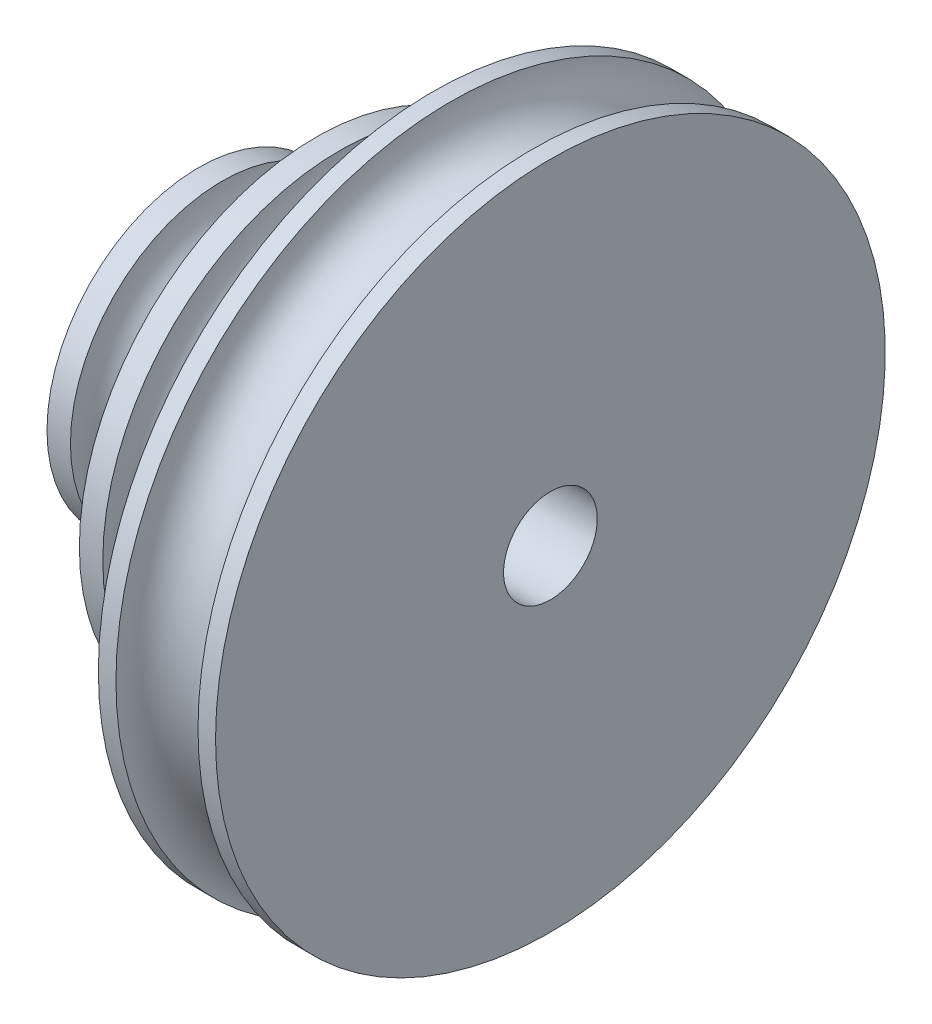
SolidWorks part; units mm, degrees
ref_plane "前视基准面" through (0, 0, 0) normal (0, 0, 1) x (1, 0, 0)
ref_plane "上视基准面" through (0, 0, 0) normal (0, 1, 0) x (1, 0, 0)
ref_plane "右视基准面" through (0, 0, 0) normal (1, 0, 0) x (0, 0, -1)
sketch "草图1" plane through (0, 0, 0) normal (0, 0, 1) x (1, 0, 0)
  line L0 (-56.8989, 20.9428) -> (82.5297, 20.9428) construction
  line L1 (-30.9942, 24.9428) -> (-30.9942, 33.8952)
  line L2 (-30.9942, 33.8952) -> (-20.9942, 33.8952)
  line L3 (-20.9942, 33.8952) -> (-20.9942, 41.1333)
  line L4 (-20.9942, 41.1333) -> (-10.9942, 41.1333)
  line L5 (-10.9942, 41.1333) -> (-10.9942, 49.5143)
  line L6 (-10.9942, 49.5143) -> (-0.9942, 49.5143)
  line L7 (-0.9942, 49.5143) -> (-0.9942, 24.9428)
  line L8 (-30.9942, 24.9428) -> (-0.9942, 24.9428)
  dimension "D1" = 4
  dimension "D2" = 30
  dimension "D3" = 10
  dimension "D4" = 10
revolve "旋转1" add sketch "草图1" angle 360 about L0
sketch "草图2" plane through (0, 0, 0) normal (0, 0, 1) x (1, 0, 0)
  line L0 (-38.5894, 20.9428) -> (11.7506, 20.9428) construction
  line L1 (-10.9942, 41.1333) -> (-20.9942, 41.1333) construction
  line L2 (-20.9942, 33.8952) -> (-30.9942, 33.8952) construction
  line L3 (-0.9942, 49.5143) -> (-10.9942, 49.5143) construction
  line L4 (-28.9942, 33.8952) -> (-20.9942, 33.8952)
  line L5 (-18.9942, 41.1333) -> (-10.9942, 41.1333)
  line L6 (-9.4942, 49.5143) -> (-2.4942, 49.5143)
  arc A0 (-18.9942, 41.1333) -> (-10.9942, 41.1333) centre (-14.9942, 41.1333) ccw
  arc A1 (-28.9942, 33.8952) -> (-20.9942, 33.8952) centre (-24.9942, 33.8952) ccw
  arc A2 (-9.4942, 49.5143) -> (-2.4942, 49.5143) centre (-5.9942, 49.5143) ccw
  dimension "D1" = 8
  dimension "D2" = 8
  dimension "D3" = 7
revolve "切除-旋转1" cut sketch "草图2" angle 360 about L0
